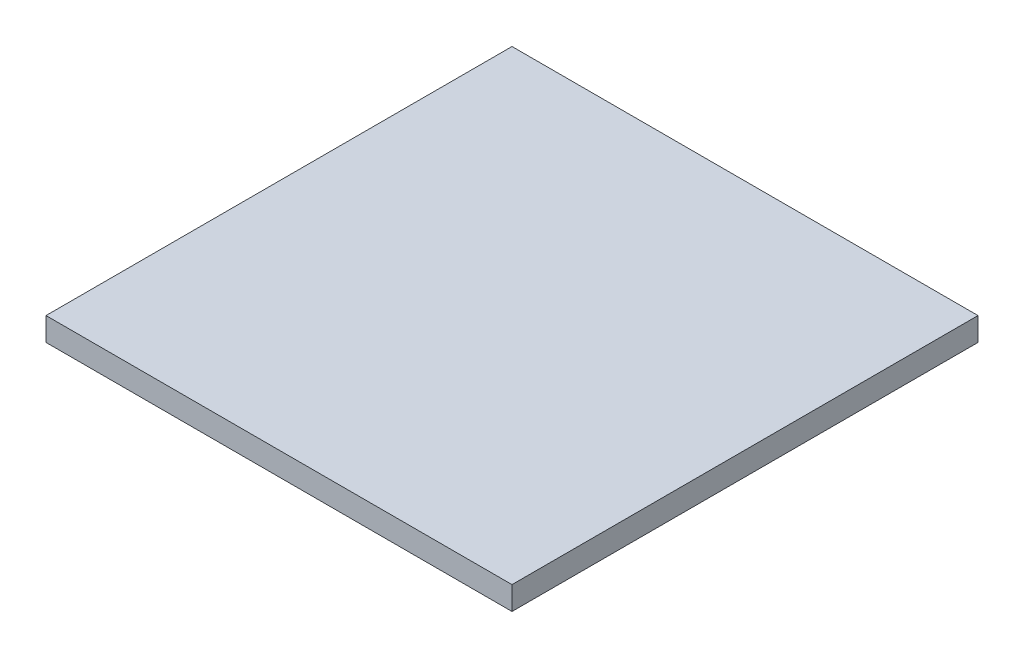
SolidWorks part; units mm, degrees
ref_plane "Alzado" through (0, 0, 0) normal (0, 0, 1) x (1, 0, 0)
ref_plane "Planta" through (0, 0, 0) normal (0, 1, 0) x (1, 0, 0)
ref_plane "Vista lateral" through (0, 0, 0) normal (1, 0, 0) x (0, 0, -1)
sketch "Croquis1" plane through (0, 0, 0) normal (0, 1, 0) x (1, 0, 0)
  line L1 (0, 0) -> (20, 0)
  line L2 (0, 0) -> (0, 20)
  line L3 (0, 20) -> (20, 20)
  line L4 (20, 0) -> (20, 20)
  dimension "D1" = 20
extrude "Saliente-Extruir1" add sketch "Croquis1" along normal blind 1
